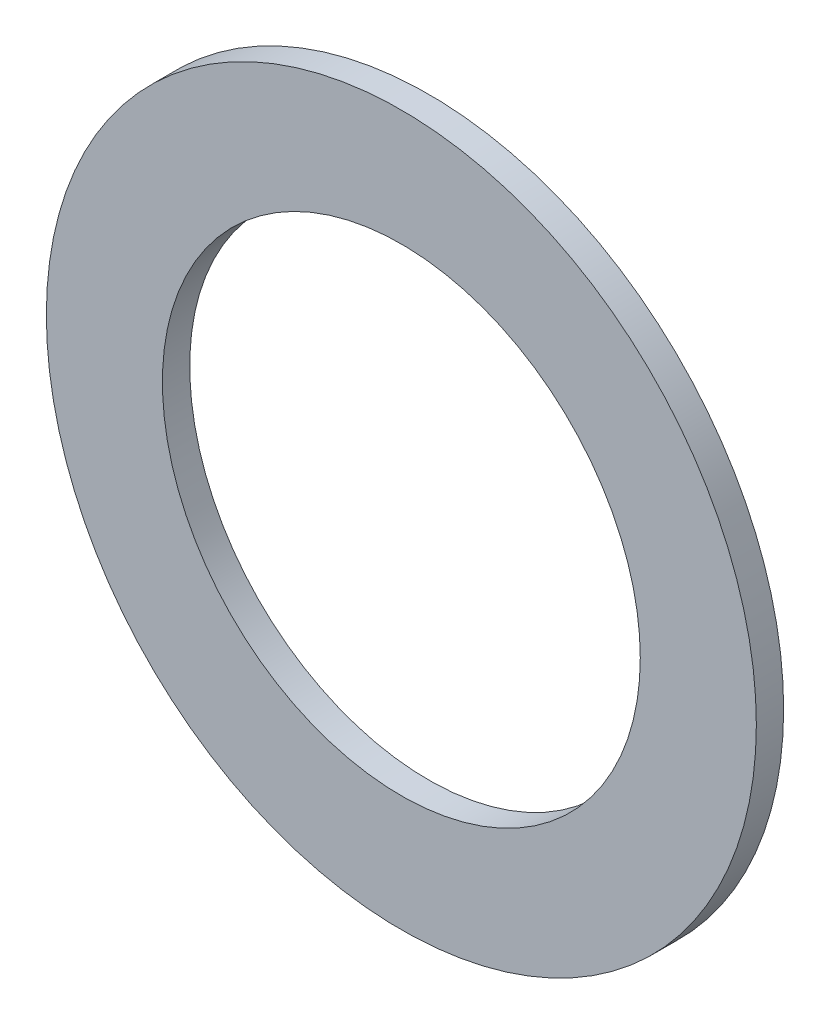
SolidWorks part; units mm, degrees
ref_plane "前视基准面" through (0, 0, 0) normal (0, 0, 1) x (1, 0, 0)
ref_plane "上视基准面" through (0, 0, 0) normal (0, 1, 0) x (1, 0, 0)
ref_plane "右视基准面" through (0, 0, 0) normal (1, 0, 0) x (0, 0, -1)
sketch "草图1" plane through (0, 0, 0) normal (0, 0, 1) x (1, 0, 0)
  circle A0 centre (0, 0) radius 17.5
  circle A1 centre (0, 0) radius 26
  dimension "D1" = 52
  dimension "D2" = 35
extrude "凸台-拉伸1" add sketch "草图1" along normal blind 2
